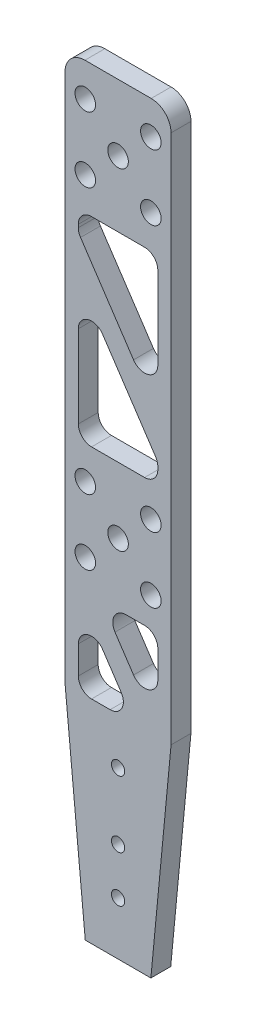
SolidWorks part; units mm, degrees
ref_plane "前视基准面" through (0, 0, 0) normal (0, 0, 1) x (1, 0, 0)
ref_plane "上视基准面" through (0, 0, 0) normal (0, 1, 0) x (1, 0, 0)
ref_plane "右视基准面" through (0, 0, 0) normal (1, 0, 0) x (0, 0, -1)
other "Configuration Table"
sketch "草图1" plane through (0, 0, 0) normal (0, 0, 1) x (1, 0, 0)
  line L0 (0, 60.2122) -> (0, -102.648) construction
  line L1 (-60.5647, 6.2167) -> (61.8958, 6.2167) construction
  line L2 (5, 16.2167) -> (-5, 16.2167)
  line L3 (-8, -66.7833) -> (-4, -108.7833)
  line L4 (0, -24.3301) -> (0, -46.8317) construction
  line L5 (8, -66.7833) -> (4, -108.7833)
  line L6 (-8, 13.2167) -> (-8, -66.7833)
  line L7 (-4, -108.7833) -> (4, -108.7833)
  line L8 (8, 13.2167) -> (8, -66.7833)
  line L12 (-27.2464, -43.7833) -> (27.2464, -43.7833) construction
  circle A0 centre (0, 6.2167) radius 7 construction
  circle A1 centre (-4.9497, 11.1665) radius 1.55
  circle A2 centre (4.9497, 11.1665) radius 1.55
  circle A3 centre (4.9497, 1.267) radius 1.55
  circle A4 centre (-4.9497, 1.267) radius 1.55
  circle A5 centre (0, -43.7833) radius 1.55
  circle A6 centre (0, -43.7833) radius 7 construction
  circle A7 centre (4.9497, -38.8335) radius 1.55
  circle A8 centre (-4.9497, -38.8335) radius 1.55
  arc A9 (8, 13.2167) -> (5, 16.2167) centre (5, 13.2167) ccw
  arc A10 (-8, 13.2167) -> (-5, 16.2167) centre (-5, 13.2167) cw
  circle A11 centre (4.9497, -48.733) radius 1.55
  circle A12 centre (-4.9497, -48.733) radius 1.55
  circle A13 centre (0, 6.2167) radius 1.55
  point P18 (0, 0)
  point P39 (0, -108.7833)
  point P44 (0, 6.2167)
  point P46 (0, -43.7833)
  dimension "D2" = 14
  dimension "D3" = 3.1
  dimension "D6" = 3.1
  dimension "D7" = 0
  dimension "D14" = 4
  dimension "D15" = 8
  dimension "D16" = 3.1
  dimension "D17" = 80
  dimension "D9" = 3
  dimension "D8" = 3.1
  dimension "D13" = 14
  dimension "D5" = 50
  dimension "D10" = 16
  dimension "D11" = 125
  dimension "D12" = 115
  dimension "D4" = 4
extrude "凸台-拉伸1" add sketch "草图1" along normal blind 3
sketch "草图2" plane through (0, 0, 0) normal (0, 0, -1) x (-1, 0, 0)
  line L0 (-14.1091, -98.7833) -> (16.5699, -98.7833)
  line L1 (16.5699, -98.7833) -> (16.5699, -119.0749)
  line L2 (16.5699, -119.0749) -> (-14.1091, -119.0749)
  line L3 (-14.1091, -119.0749) -> (-14.1091, -98.7833)
  line L4 (4, -108.7833) -> (-4, -108.7833) construction
  dimension "D1" = 10
extrude "切除-拉伸1" cut sketch "草图2" against normal blind 10
sketch "草图3" plane through (0, 0, 0) normal (0, 0, -1) x (-1, 0, 0)
  line L0 (4.9524, -98.7833) -> (-4.9524, -98.7833) construction
  circle A0 centre (0, -83.7833) radius 1
  circle A1 centre (0, -90.7833) radius 1
  circle A2 centre (0, -73.7833) radius 1
  dimension "D3" = 2
  dimension "D1" = 15
  dimension "D2" = 8
  dimension "D4" = 25
extrude "切除-拉伸2" cut sketch "草图3" against normal blind 20
sketch "草图4" plane through (0, 0, 0) normal (0, 0, -1) x (-1, 0, 0)
  line L0 (8, 13.2167) -> (8, -66.7833) construction
  line L1 (-6, -3.733) -> (6, -3.733)
  line L2 (-6, -3.733) -> (-6, -24.7833)
  line L3 (-6, -33.8335) -> (6, -33.8335)
  line L4 (6, -3.733) -> (6, -6.7833)
  line L9 (-8, -66.7833) -> (-8, 13.2167) construction
  line L10 (-6, -18.7833) -> (6, -18.7833) construction
  line L11 (-6, -30.7833) -> (6, -12.7833)
  line L12 (-6, -24.7833) -> (6, -6.7833)
  line L13 (6, -53.9765) -> (-6, -71.9765)
  line L14 (-6, -53.1697) -> (6, -53.1697)
  line L15 (-6, -53.1697) -> (-6, -66.7833)
  line L16 (-6, -66.7833) -> (6, -66.7833)
  line L17 (6, -53.1697) -> (6, -66.7833)
  line L18 (6, -47.9765) -> (-6, -65.9765)
  line L19 (-6, -59.9765) -> (6, -59.9765) construction
  line L20 (6, -12.7833) -> (6, -33.8335)
  line L21 (-6, -30.7833) -> (-6, -33.8335)
  circle A0 centre (4.9497, 1.267) radius 1.55 construction
  circle A1 centre (4.9497, -38.8335) radius 1.55 construction
  circle A2 centre (4.9497, -48.733) radius 1.55 construction
  dimension "D1" = 2
  dimension "D2" = 2
  dimension "D3" = 5
  dimension "D4" = 5
  dimension "D5" = 6
  dimension "D6" = 6
  dimension "D7" = 6
  dimension "D8" = 2
  dimension "D9" = 2
  dimension "D10" = 4.4367
  dimension "D11" = 6
  dimension "D12" = 6
extrude "切除-拉伸3" cut sketch "草图4" against normal through all contours L2 L10 L12 L4 L1 | L10 L2 L12 | L11 L10 L4 | L10 L11 L2 L3 L4 | L18 L14 L15 | L17 L13 L16
fillet "圆角1" radius 2 14 edges at (-6, -66.7833, 1.5) (2.5378, -66.7833, 1.5) (-6, -53.9765, 1.5) (6, -65.9765, 1.5) (-2.5378, -53.1697, 1.5) (6, -53.1697, 1.5) (-6, -33.8335, 1.5) (6, -33.8335, 1.5) (6, -30.7833, 1.5) (-6, -12.7833, 1.5) (6, -24.7833, 1.5) (-6, -6.7833, 1.5) (-6, -3.733, 1.5) (6, -3.733, 1.5)
